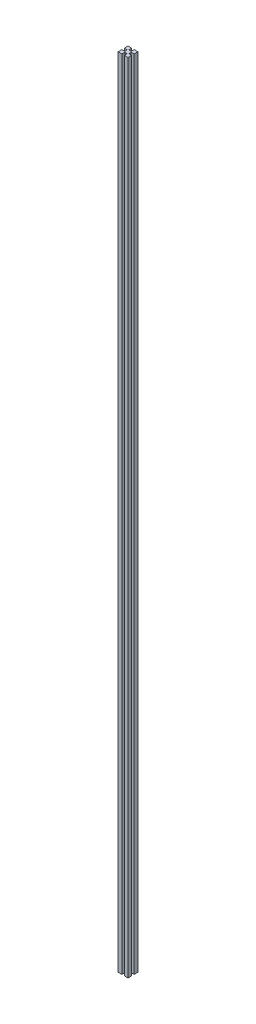
SolidWorks part; units mm, degrees
ref_plane "Front Plane" through (0, 0, 0) normal (0, 0, 1) x (1, 0, 0)
ref_plane "Top Plane" through (0, 0, 0) normal (0, 1, 0) x (1, 0, 0)
ref_plane "Right Plane" through (0, 0, 0) normal (1, 0, 0) x (0, 0, -1)
sketch "Sketch1" plane through (0, 0, 0) normal (0, 1, 0) x (1, 0, 0)
  line L1 (-10, -10) -> (10, -10)
  line L2 (-10, -10) -> (-10, 10)
  line L3 (-10, 10) -> (10, 10)
  line L4 (10, -10) -> (10, 10)
  line L5 (-10, -10) -> (10, 10) construction
  line L6 (-10, 10) -> (10, -10) construction
  point P0 (0, 0)
  dimension "D1" = 20
  dimension "D2" = 20
extrude "Boss-Extrude1" add sketch "Sketch1" along normal blind 800.1 and the other way blind 800.1
sketch "Sketch2" plane through (0, 0, 0) normal (0, 1, 0) x (1, 0, 0)
  line L0 (-2.5, 4) -> (2.5, 4)
  line L1 (-2.5, 4) -> (-2.5, 16)
  line L2 (-2.5, 16) -> (2.5, 16)
  line L3 (2.5, 4) -> (2.5, 16)
  line L4 (-2.5, 4) -> (2.5, 16) construction
  line L5 (-2.5, 16) -> (2.5, 4) construction
  line L6 (4, 2.5) -> (16, 2.5)
  line L7 (4, 2.5) -> (4, -2.5)
  line L8 (4, -2.5) -> (16, -2.5)
  line L9 (16, 2.5) -> (16, -2.5)
  line L10 (4, 2.5) -> (16, -2.5) construction
  line L11 (4, -2.5) -> (16, 2.5) construction
  line L12 (-10, 10) -> (10, -10) construction
  line L13 (-16, 2.5) -> (-4, -2.5) construction
  line L14 (-4, 2.5) -> (-16, -2.5) construction
  line L15 (-4, -2.5) -> (-16, -2.5)
  line L16 (-16, 2.5) -> (-16, -2.5)
  line L17 (-4, 2.5) -> (-16, 2.5)
  line L18 (-4, 2.5) -> (-4, -2.5)
  line L19 (2.5, -4) -> (2.5, -16)
  line L20 (2.5, -4) -> (-2.5, -16) construction
  line L21 (-2.5, -4) -> (2.5, -16) construction
  line L22 (-2.5, -16) -> (2.5, -16)
  line L23 (-2.5, -4) -> (2.5, -4)
  line L24 (-2.5, -4) -> (-2.5, -16)
  line L25 (-10, 10) -> (-10, -10) construction
  line L26 (10, -10) -> (10, 10) construction
  line L27 (-10, -10) -> (10, -10) construction
  line L28 (10, 10) -> (-10, 10) construction
  point P0 (0, 10)
  point P5 (10, 0)
  point P16 (-10, 0)
  point P21 (0, -10)
  dimension "D1" = 5
  dimension "D2" = 12
  dimension "D3" = 5
  dimension "D4" = 12
extrude "Cut-Extrude1" cut sketch "Sketch2" against normal through all both and the other way through all
